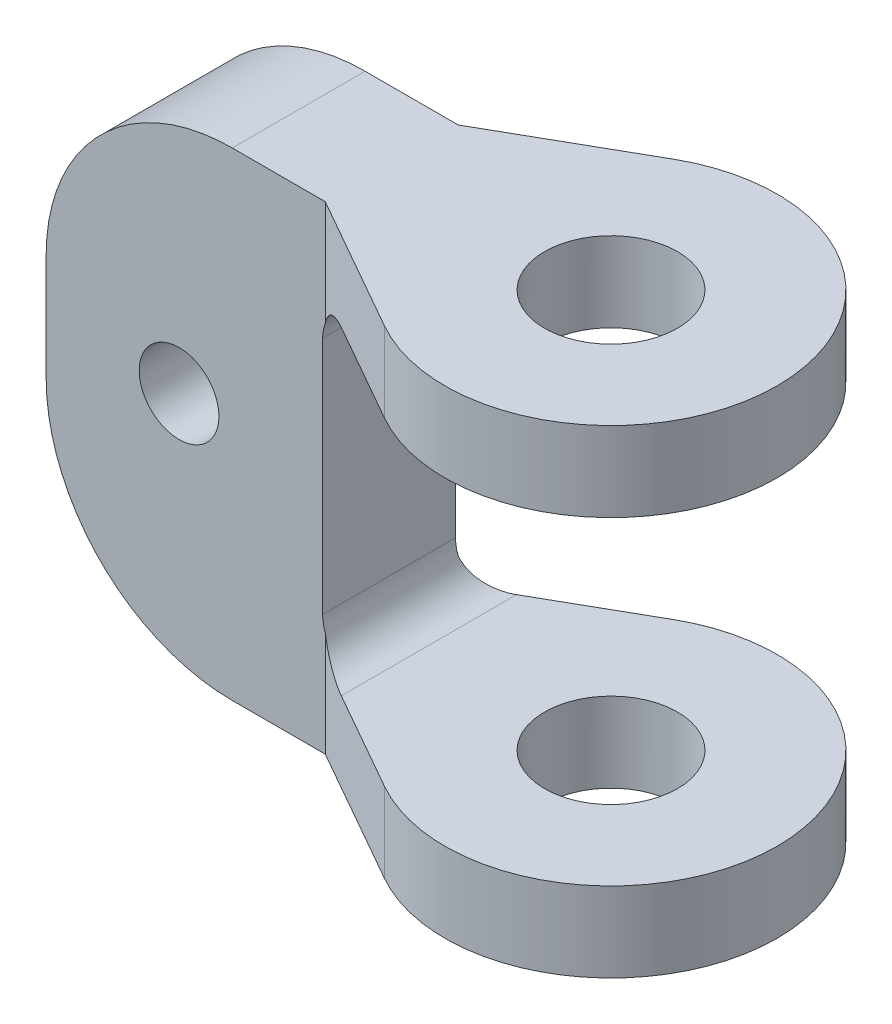
SolidWorks part; units mm, degrees
ref_plane "Alzado" through (0, 0, 0) normal (0, 0, 1) x (1, 0, 0)
ref_plane "Planta" through (0, 0, 0) normal (0, 1, 0) x (1, 0, 0)
ref_plane "Vista lateral" through (0, 0, 0) normal (1, 0, 0) x (0, 0, -1)
sketch "Croquis1" plane through (0, 0, 0) normal (0, 0, 1) x (1, 0, 0)
  line L0 (11.25, 14.1) -> (11.25, 11.1)
  line L1 (5.75, -0.9) -> (11.25, -0.9)
  line L2 (-1.25, 6.1) -> (-1.25, 10.1)
  line L3 (5.75, 17.1) -> (11.25, 17.1)
  line L4 (11.25, 11.1) -> (23.75, 11.1) construction
  line L5 (-1.25, -0.9) -> (1.25, 0.9) construction
  line L6 (-1.25, 17.1) -> (-1.0254, 14.0276) construction
  line L7 (11.25, 11.1) -> (11.25, 5.1)
  line L8 (-1.25, 8.1) -> (23.75, 8.1) construction
  line L9 (23.75, -0.9) -> (23.75, 2.1)
  line L10 (11.25, 5.1) -> (11.25, 2.1)
  line L11 (23.75, 11.1) -> (23.75, 14.1) construction
  line L12 (23.75, 14.1) -> (11.25, 14.1)
  line L13 (11.25, 17.1) -> (-1.25, 17.1) construction
  line L14 (11.25, -0.9) -> (23.75, -0.9)
  line L15 (23.75, 2.1) -> (11.25, 2.1)
  line L16 (11.25, 17.1) -> (23.75, 17.1)
  line L17 (23.75, 17.1) -> (23.75, 14.1)
  circle A0 centre (3.75, 8.1) radius 1.5
  arc A1 (-1.25, 10.1) -> (5.75, 17.1) centre (5.75, 10.1) cw
  arc A2 (5.75, -0.9) -> (-1.25, 6.1) centre (5.75, 6.1) cw
  point P0 (0, 0)
  dimension "D6" = 3
  dimension "D4" = 7
  dimension "D2" = 18
  dimension "D3" = 12.5
  dimension "D7" = 5
  dimension "D8" = 9
  dimension "D10" = 3
  dimension "D11" = 3
extrude "Saliente-Extruir1" add sketch "Croquis1" along normal blind 15
sketch "Croquis2" plane through (0, 0, 0) normal (0, 1, 0) x (1, 0, 0)
  line L3 (17.5, -1.25) -> (11.25, 0)
  line L4 (17.5, -13.75) -> (11.25, -15)
  line L5 (11.25, -15) -> (11.25, -17.9613)
  line L6 (11.25, -17.9613) -> (29.6635, -17.9613)
  line L7 (29.6635, -17.9613) -> (29.6635, 1.8686)
  line L8 (29.6635, 1.8686) -> (11.1263, 1.8686)
  line L9 (11.1263, 1.8686) -> (11.25, 0)
  circle A0 centre (17.5, -7.5) radius 2.5
  arc A1 (17.5, -13.75) -> (17.5, -1.25) centre (17.5, -7.5) ccw
  dimension "D1" = 5
extrude "Cortar-Extruir1" cut sketch "Croquis2" along normal mid plane 40
sketch "Croquis3" plane through (0, 17.1, 0) normal (0, 1, 0) x (1, 0, 0)
  line L0 (-1.25, -15) -> (-1.25, 0) construction
  line L1 (-2.0507, -10) -> (9.25, -10)
  line L2 (-9.9732, -8.842) -> (-9.9732, -6.158)
  line L3 (-2.0507, -5) -> (9.25, -5)
  line L4 (17.5, -1.25) -> (17.5, 1.6133)
  line L5 (-9.9732, -8.842) -> (-1.25, -7.5) construction
  line L6 (-9.9732, -6.158) -> (-1.25, -7.5) construction
  line L7 (17.5, -1.25) -> (17.5, -13.75) construction
  line L8 (9.25, -5) -> (14.4117, -2.0663)
  line L9 (-9.9732, -7.5) -> (-6.6938, -7.5) construction
  line L10 (17.5, 1.6133) -> (-2.0507, 1.6133)
  line L11 (-2.0507, 1.6133) -> (-2.0507, -5)
  line L12 (-2.0507, -10) -> (-2.3251, -18.2596)
  line L13 (-2.3251, -18.2596) -> (20.8404, -18.2596)
  line L14 (20.8404, -18.2596) -> (17.5, -13.75)
  line L15 (5.25, 0) -> (2.25, 0) construction
  line L16 (9.25, -10) -> (14.4117, -12.9337)
  arc A0 (14.4117, -12.9337) -> (17.5, -13.75) centre (17.5, -7.5) ccw
  arc A2 (17.5, -1.25) -> (14.4117, -2.0663) centre (17.5, -7.5) ccw
  point P0 (-1.25, -7.5)
  point P12 (3.75, 0)
  dimension "D3" = 5
  dimension "D4" = 2
extrude "Cortar-Extruir2" cut sketch "Croquis3" against normal blind 22
ref_plane "Plano1" through (0, 0, 7.5) normal (0, 0, 1) x (1, 0, 0)
sketch "Croquis4" plane through (0, 0, 10) normal (0, 0, 1) x (1, 0, 0)
  line L0 (11.25, 14.1) -> (14.4117, 14.1) construction
  line L1 (12.8309, 14.1) -> (9.15, 14.1)
  line L2 (12.8309, 14.1) -> (12.8309, 2.1)
  line L3 (12.8309, 2.1) -> (9.15, 2.1)
  line L4 (9.15, 14.1) -> (9.15, 2.1)
  line L5 (14.4117, 2.1) -> (11.25, 2.1) construction
  line L6 (11.25, 2.1) -> (11.25, 14.1) construction
  dimension "D1" = 2.1
extrude "Cortar-Extruir3" cut sketch "Croquis4" against normal mid plane 20
fillet "Redondeo1" radius 1.5 2 edges at (9.15, 2.1, 7.5) (9.15, 14.1, 7.5)
